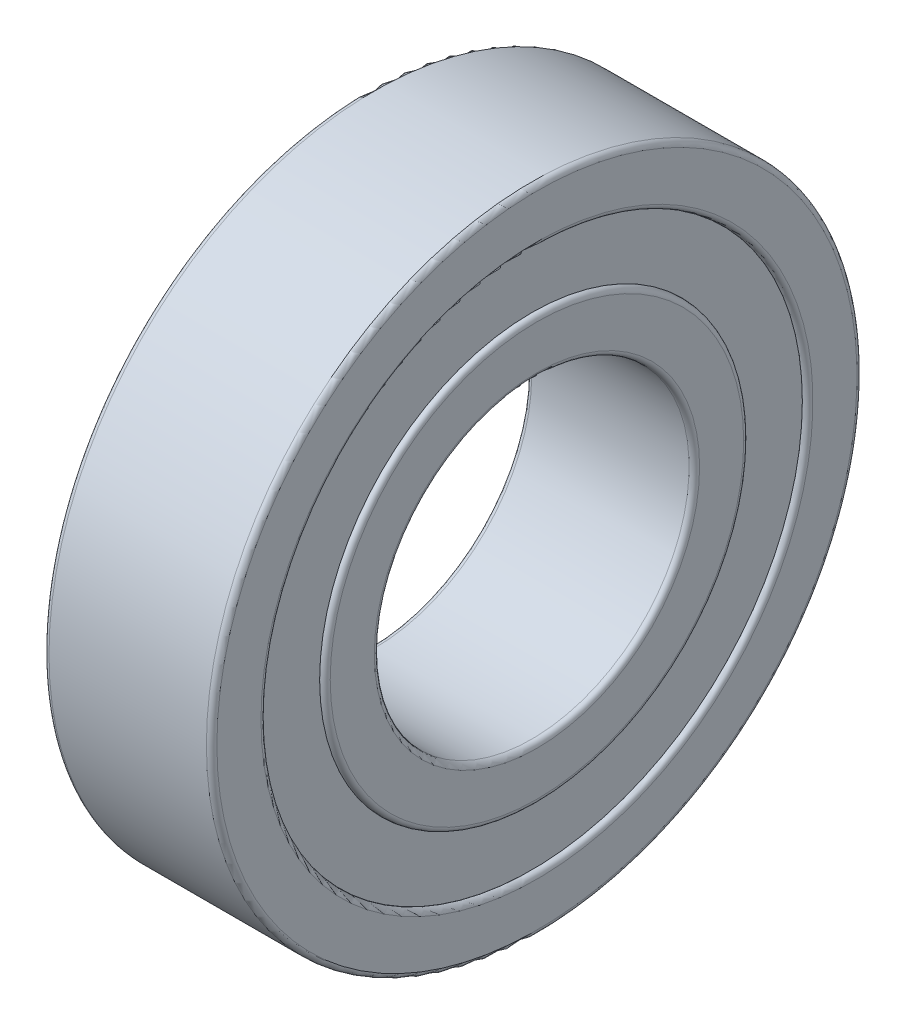
SolidWorks part; units mm, degrees
material "1350 Legierung"
ref_plane "Ebene1" through (0, 0, 0) normal (0, 0, 1) x (1, 0, 0)
ref_plane "Ebene2" through (0, 0, 0) normal (0, 1, 0) x (1, 0, 0)
ref_plane "Ebene3" through (0, 0, 0) normal (1, 0, 0) x (0, 0, -1)
sketch "Skizze1" plane through (0, 0, 0) normal (0, 0, 1) x (1, 0, 0)
  line L0 (8, 15) -> (-8, 15)
  line L1 (8, 15) -> (8, 20.2)
  line L2 (-8, 20.2) -> (-5.3179, 20.2)
  line L3 (-8, 20.2) -> (-8, 15)
  line L4 (8, 25.8) -> (5.3179, 25.8)
  line L5 (8, 25.8) -> (8, 31)
  line L6 (-8, 31) -> (8, 31)
  line L7 (-8, 31) -> (-8, 25.8)
  line L8 (-18.6811, 0) -> (1.8121, 0) construction
  line L9 (5.3179, 20.2) -> (8, 20.2)
  line L10 (-5.3179, 25.8) -> (-8, 25.8)
  line L11 (0, 31) -> (0, 15) construction
  arc A0 (-5.3179, 25.8) -> (-5.3179, 20.2) centre (0, 23) ccw
  arc A1 (5.3179, 20.2) -> (5.3179, 25.8) centre (0, 23) ccw
  circle A2 centre (0, 23) radius 6
  dimension "D5" = 0.01
  dimension "D6" = 12
  dimension "D1" = 30
  dimension "D2" = 62
  dimension "D3" = 16
  dimension "D4" = 40.4
revolve "Basis-Rotation" add sketch "Skizze1" angle 360 about L8
fillet "Verrundung1" radius 0.5 8 edges at (8, 0, 15) (8, 0, 20.2) (8, 0, 25.8) (-8, 0, 25.8) (-8, 0, 15) (-8, 0, 20.2) (-8, 0, 31) (8, 0, 31)
sketch "Skizze4" plane through (0, 0, 0) normal (0, 0, 1) x (1, 0, 0)
  line L0 (-5.3179, 20.2) -> (-7.5, 20.2) construction
  line L1 (-7.5, 25.79) -> (-7, 25.79)
  line L2 (-7.5, 25.79) -> (-7.5, 20.21)
  line L3 (-7.5, 20.21) -> (-7, 20.21)
  line L4 (-7, 25.79) -> (-7, 20.21)
  line L5 (-5.3179, 25.8) -> (-7.5, 25.8) construction
  line L6 (0, 0) -> (-27.9639, 0) construction
  line L7 (0, 0) -> (0, 31.7856) construction
  line L8 (7, 25.79) -> (7, 20.21)
  line L9 (7.5, 20.21) -> (7, 20.21)
  line L10 (7.5, 25.79) -> (7.5, 20.21)
  line L11 (7.5, 25.79) -> (7, 25.79)
  dimension "D1" = 0.01
  dimension "D2" = 0.01
  dimension "D3" = 0.5
revolve "Rotation1" add sketch "Skizze4" angle 360 about L6
